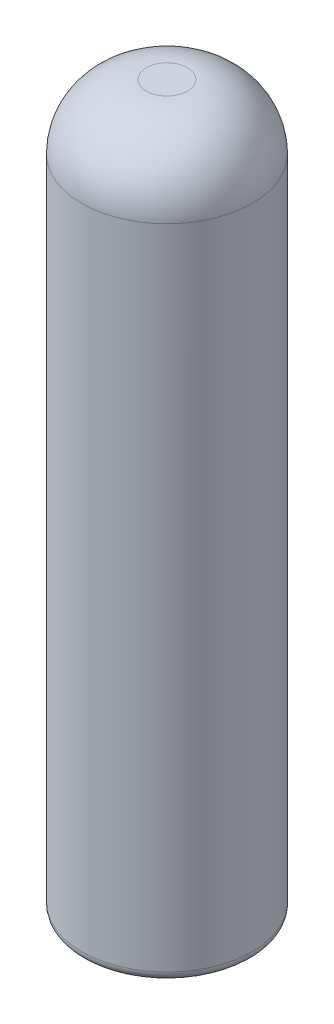
SolidWorks part; units mm, degrees
ref_plane "Front Plane" through (0, 0, 0) normal (0, 0, 1) x (1, 0, 0)
ref_plane "Top Plane" through (0, 0, 0) normal (0, 1, 0) x (1, 0, 0)
ref_plane "Right Plane" through (0, 0, 0) normal (1, 0, 0) x (0, 0, -1)
sketch "Sketch1" plane through (0, 0, 0) normal (0, 0, 1) x (1, 0, 0)
  line L0 (0, 0) -> (0, -240.7316) construction
  line L1 (0, 0) -> (-85.5, 0)
  line L2 (-85.5, 0) -> (-85.5, 660)
  line L3 (-20.5, 725) -> (0, 725)
  line L4 (0, 725) -> (0, 0)
  arc A0 (-85.5, 660) -> (-20.5, 725) centre (-20.5, 660) cw
  dimension "D3" = 65
  dimension "D1" = 171
  dimension "D2" = 725
revolve "Revolve1" add sketch "Sketch1" angle 360 about L0
fillet "Fillet1" radius 10 1 edges at (0, 0, 85.5)
